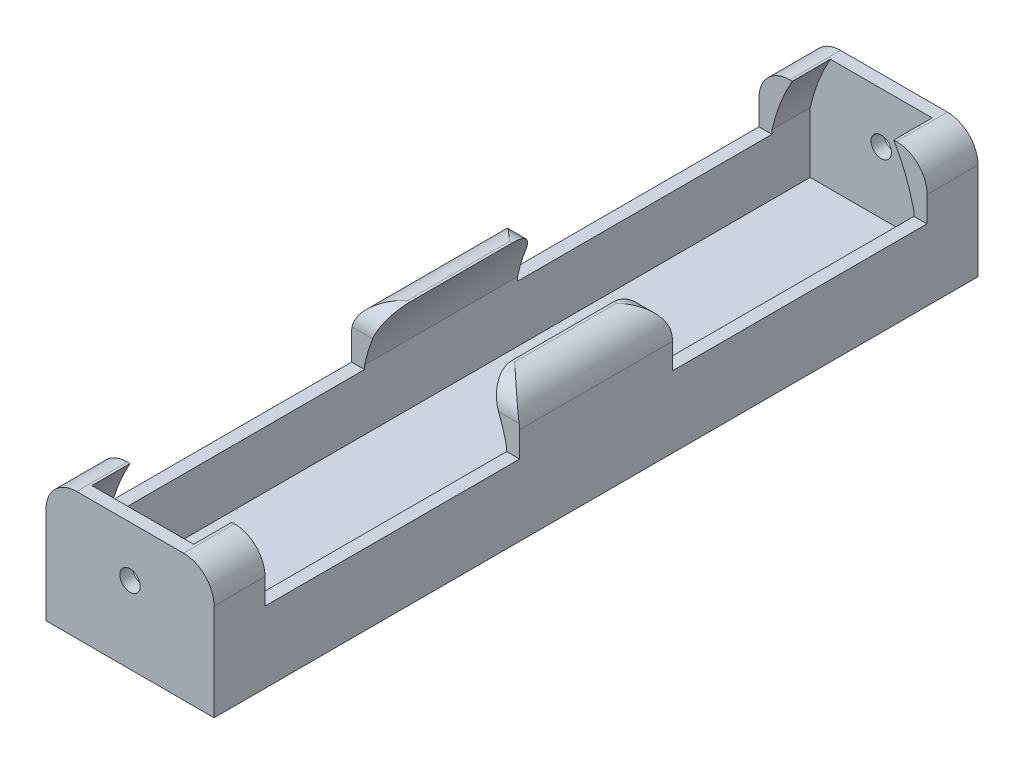
SolidWorks part; units mm, degrees
ref_plane "Front Plane" through (0, 0, 0) normal (0, 0, 1) x (1, 0, 0)
ref_plane "Top Plane" through (0, 0, 0) normal (0, 1, 0) x (1, 0, 0)
ref_plane "Right Plane" through (0, 0, 0) normal (1, 0, 0) x (0, 0, -1)
sketch "Sketch1" plane through (0, 0, 0) normal (0, 0, 1) x (1, 0, 0)
  line L0 (0, 1.3348) -> (0, -0.2163) construction
  line L1 (-2.1, 1.3348) -> (2.1, 1.3348)
  line L2 (3.3, 0.1348) -> (3.3, -3.6652)
  line L3 (3.3, -3.6652) -> (-3.3, -3.6652)
  line L4 (-3.3, -3.6652) -> (-3.3, 0.1348)
  arc A0 (2.1, 1.3348) -> (3.3, 0.1348) centre (2.1, 0.1348) cw
  arc A1 (-3.3, 0.1348) -> (-2.1, 1.3348) centre (-2.1, 0.1348) cw
  dimension "D4" = 1.2
  dimension "D1" = 5
  dimension "D2" = 3.3
  dimension "D3" = 3.3
extrude "Boss-Extrude1" add sketch "Sketch1" along normal blind 30
sketch "Sketch2" plane through (0, 0, 0) normal (1, 0, 0) x (0, 0, -1)
  line L0 (-2, 1.3348) -> (-2, -0.8652)
  line L1 (-30, 1.3348) -> (0, 1.3348) construction
  line L2 (-2, -0.8652) -> (-12, -0.8652)
  line L3 (-12, -0.8652) -> (-12, 0.3348)
  line L4 (0, 0.1348) -> (0, -3.6652) construction
  line L5 (-30, -3.6652) -> (0, -3.6652) construction
  line L6 (-15, 1.3348) -> (-15, -6.4401) construction
  line L7 (-17, 1.3348) -> (-28, 1.3348)
  line L8 (-18, -0.8652) -> (-18, 0.3348)
  line L9 (-28, -0.8652) -> (-18, -0.8652)
  line L10 (-28, 1.3348) -> (-28, -0.8652)
  line L11 (-2, 1.3348) -> (-13, 1.3348)
  arc A0 (-12, 0.3348) -> (-13, 1.3348) centre (-13, 0.3348) ccw
  arc A1 (-18, 0.3348) -> (-17, 1.3348) centre (-17, 0.3348) cw
  point P14 (-12, 1.3348)
  point P21 (-18, 1.3348)
  dimension "D4" = 1
  dimension "D1" = 2
  dimension "D2" = 10
  dimension "D3" = 2.8
extrude "Cut-Extrude1" cut sketch "Sketch2" against normal blind 7 and the other way blind 20
sketch "Sketch3" plane through (0, 0, 0) normal (0, 0, -1) x (-1, 0, 0)
  line L0 (-2.7895, -3.0825) -> (2.7895, -3.0825)
  line L1 (2.7895, -3.0825) -> (2.7895, -0.7111)
  line L2 (0, 0) -> (0, -2.2536) construction
  line L3 (-2.7895, -3.0825) -> (-2.7895, -0.7111)
  line L4 (-2.1, 1.3348) -> (2.1, 1.3348) construction
  line L5 (-1.9966, 1.3348) -> (1.9966, 1.3348)
  spline S0 degree 2 poles (2.7895, -0.7111) (2.5471, 0.3727) (1.9966, 1.3348) knots 0 0 0 1 1 1
  spline S1 degree 2 poles (-2.7895, -0.7111) (-2.5471, 0.3727) (-1.9966, 1.3348) knots 0 0 0 1 1 1
extrude "Cut-Extrude3" cut sketch "Sketch3" against normal blind 29 from offset 0.5 offset against normal yes
sketch "Sketch4" plane through (0, 0, 0) normal (0, 0, -1) x (-1, 0, 0)
  circle A0 centre (0, -0.6462) radius 0.4
  dimension "D1" = 0.8
extrude "Cut-Extrude4" cut sketch "Sketch4" against normal blind 33
sketch "Sketch5" plane through (0, 0, 29.5) normal (0, 0, -1) x (-1, 0, 0)
  line L4 (2.7895, -3.0825) -> (2.7895, -0.7111)
  line L5 (1.9966, 1.3348) -> (-1.9966, 1.3348)
  line L6 (-2.7895, -0.7111) -> (-2.7895, -3.0825)
  line L7 (-2.7895, -3.0825) -> (2.7895, -3.0825)
  line L8 (2.7895, -3.0825) -> (2.7895, -0.7111)
  line L9 (1.9966, 1.3348) -> (-1.9966, 1.3348)
  line L10 (-2.7895, -0.7111) -> (-2.7895, -3.0825)
  line L11 (-2.7895, -3.0825) -> (2.7895, -3.0825)
  parabola Q2 (2.7895, -0.7111) -> (1.9966, 1.3348) focus (-0.9269, -0.9496) apex (2.4533, 0.3851)
  parabola Q3 (-1.9966, 1.3348) -> (-2.7895, -0.7111) focus (0.9269, -0.9496) apex (-2.4533, 0.3851)
  parabola Q4 (2.7895, -0.7111) -> (1.9966, 1.3348) focus (-0.9269, -0.9496) apex (2.4533, 0.3851)
  parabola Q5 (-1.9966, 1.3348) -> (-2.7895, -0.7111) focus (0.9269, -0.9496) apex (-2.4533, 0.3851)
  dimension "D1" = 0
sketch "Sketch6" plane through (0, 0, 0) normal (0, 0, 1) x (1, 0, 0)
  circle A2 centre (0, -0.6462) radius 0.9
  circle A3 centre (0, -0.6462) radius 0.9
  dimension "D1" = 0.5
